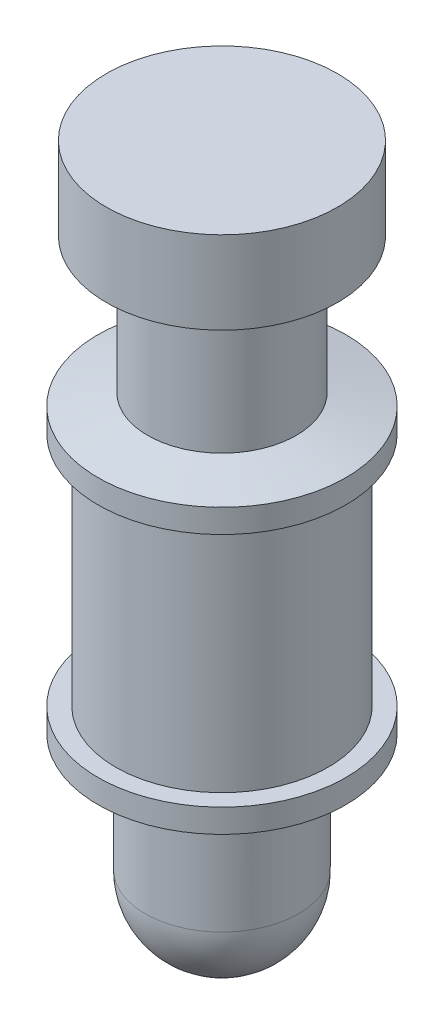
SolidWorks part; units mm, degrees
material "Nylon 101"
ref_plane "Alzado" through (0, 0, 0) normal (0, 0, 1) x (1, 0, 0)
ref_plane "Planta" through (0, 0, 0) normal (0, 1, 0) x (1, 0, 0)
ref_plane "Vista lateral" through (0, 0, 0) normal (1, 0, 0) x (0, 0, -1)
sketch "Sketch1" plane through (0, 0, 0) normal (0, 0, 1) x (1, 0, 0)
  line L0 (0, 3.5) -> (9.8, 3.5)
  line L1 (9.8, 3.5) -> (9.8, -3.5)
  line L2 (9.8, -3.5) -> (6.3, -5)
  line L3 (6.3, -5) -> (6.3, -15)
  line L4 (6.3, -15) -> (10.5, -16)
  line L5 (10.5, -16) -> (10.5, -18)
  line L6 (10.5, -18) -> (9, -18)
  line L7 (9, -18) -> (9, -38)
  line L8 (9, -38) -> (10.5, -38)
  line L9 (10.5, -38) -> (10.5, -40)
  line L10 (10.5, -40) -> (6.5, -41)
  line L11 (6.5, -41) -> (6.5, -50)
  line L12 (6.5, -50) -> (0, -50)
  line L13 (0, -50) -> (0, 3.5)
  line L14 (0, -54) -> (0, 7.5) construction
revolve "Cabeza_cuello_tambor" add sketch "Sketch1" angle 360 about L14
sketch "Sketch2" plane through (0, 0, 0) normal (0, 0, 1) x (1, 0, 0)
  line L0 (0, -56.5) -> (0, -43.5)
  line L1 (0, -60.5) -> (0, -39.5) construction
  arc A0 (0, -43.5) -> (0, -56.5) centre (0, -50) cw
revolve "Union_diafisis" add sketch "Sketch2" angle 360 about L1
